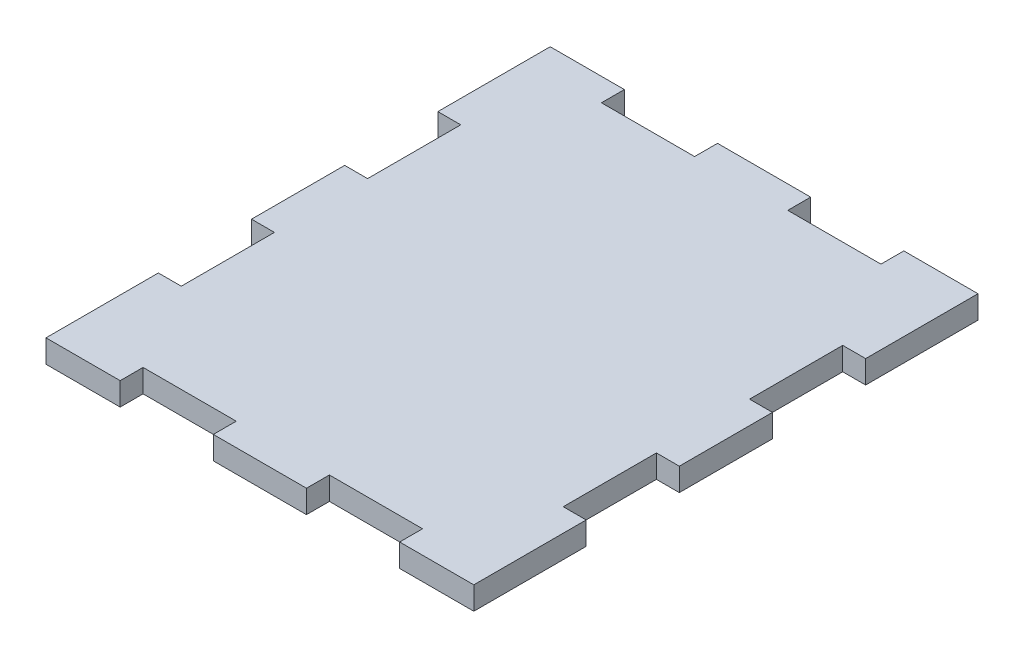
SolidWorks part; units mm, degrees
ref_plane "Front Plane" through (0, 0, 0) normal (0, 0, 1) x (1, 0, 0)
ref_plane "Top Plane" through (0, 0, 0) normal (0, 1, 0) x (1, 0, 0)
ref_plane "Right Plane" through (0, 0, 0) normal (1, 0, 0) x (0, 0, -1)
sketch "Sketch2" plane through (0, 0, 0) normal (0, 1, 0) x (1, 0, 0)
  line L0 (0, 270) -> (0, 240.585)
  line L1 (0, 240.585) -> (6, 240.585)
  line L2 (6, 240.585) -> (6, 216.195)
  line L3 (6, 216.195) -> (0, 216.195)
  line L4 (0, 216.195) -> (0, 191.805)
  line L5 (0, 191.805) -> (6, 191.805)
  line L6 (6, 191.805) -> (6, 167.415)
  line L7 (6, 167.415) -> (0, 167.415)
  line L8 (0, 167.415) -> (0, 143.025)
  line L9 (0, 143.025) -> (0, 138)
  line L10 (0, 138) -> (19.415, 138)
  line L11 (19.415, 138) -> (19.415, 144)
  line L12 (19.415, 144) -> (43.805, 144)
  line L13 (43.805, 144) -> (43.805, 138)
  line L14 (43.805, 138) -> (68.195, 138)
  line L15 (68.195, 138) -> (68.195, 144)
  line L16 (68.195, 144) -> (92.585, 144)
  line L17 (92.585, 144) -> (92.585, 138)
  line L18 (92.585, 138) -> (112, 138)
  line L19 (112, 138) -> (112, 167.415)
  line L20 (112, 167.415) -> (106, 167.415)
  line L21 (106, 167.415) -> (106, 191.805)
  line L22 (106, 191.805) -> (112, 191.805)
  line L23 (112, 191.805) -> (112, 216.195)
  line L24 (112, 216.195) -> (106, 216.195)
  line L25 (106, 216.195) -> (106, 240.585)
  line L26 (106, 240.585) -> (112, 240.585)
  line L27 (112, 240.585) -> (112, 264.975)
  line L28 (112, 264.975) -> (112, 270)
  line L29 (112, 270) -> (92.585, 270)
  line L30 (92.585, 270) -> (92.585, 264)
  line L31 (92.585, 264) -> (68.195, 264)
  line L32 (68.195, 264) -> (68.195, 270)
  line L33 (68.195, 270) -> (43.805, 270)
  line L34 (43.805, 270) -> (43.805, 264)
  line L35 (43.805, 264) -> (19.415, 264)
  line L36 (19.415, 264) -> (19.415, 270)
  line L37 (19.415, 270) -> (0, 270)
extrude "Boss-Extrude1" add sketch "Sketch2" along normal blind 6
